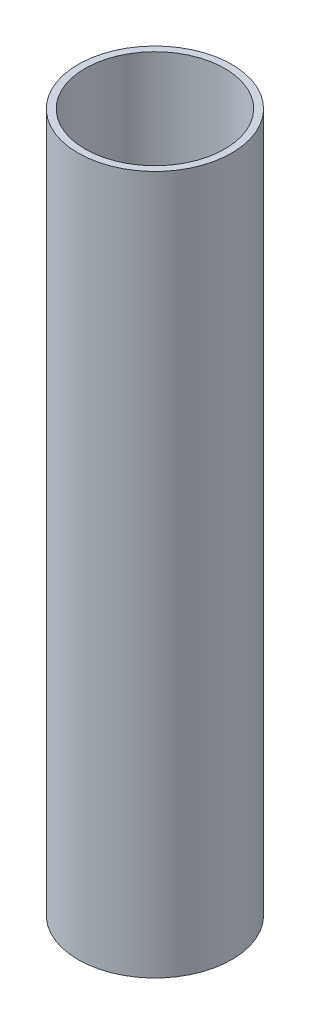
SolidWorks part; units mm, degrees
material "ABS PC"
ref_plane "前视基准面" through (0, 0, 0) normal (0, 0, 1) x (1, 0, 0)
ref_plane "上视基准面" through (0, 0, 0) normal (0, 1, 0) x (1, 0, 0)
ref_plane "右视基准面" through (0, 0, 0) normal (1, 0, 0) x (0, 0, -1)
sketch "草图1" plane through (0, 0, 0) normal (0, 1, 0) x (1, 0, 0)
  circle A0 centre (0, 0) radius 55
  circle A1 centre (0, 0) radius 50
  dimension "D1" = 110
  dimension "D2" = 100
extrude "凸台-拉伸1" add sketch "草图1" along normal blind 500
